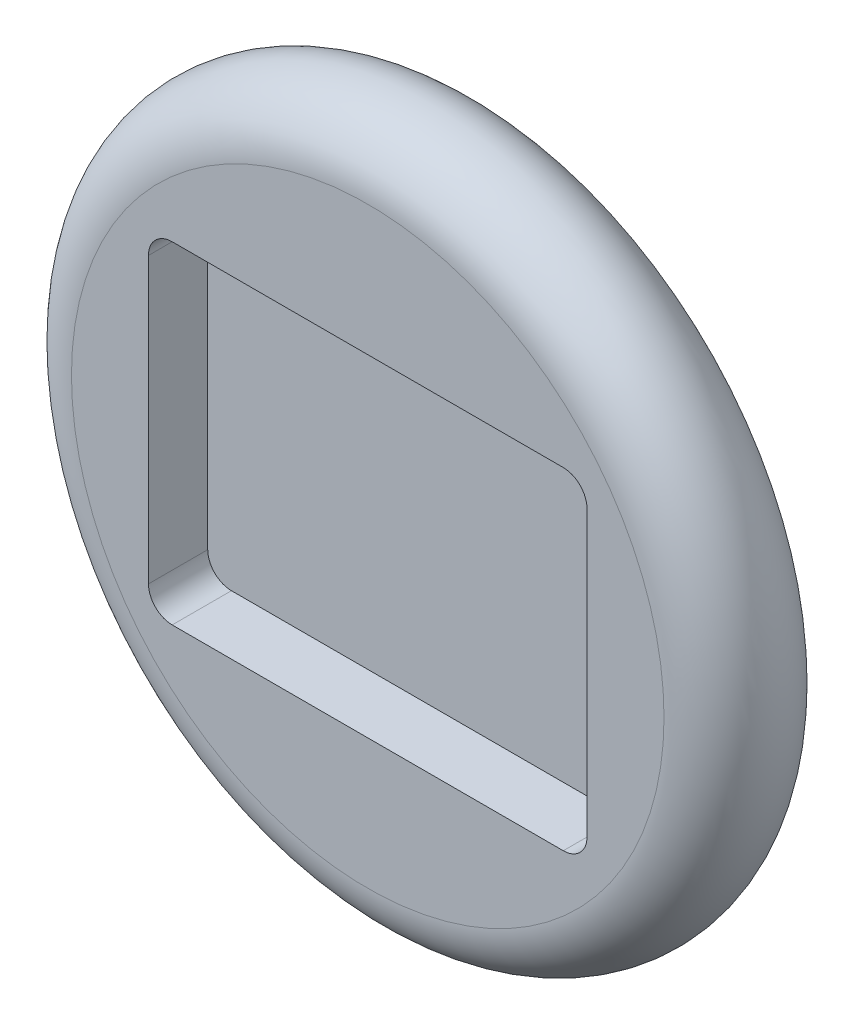
SolidWorks part; units mm, degrees
ref_plane "Front Plane" through (0, 0, 0) normal (0, 0, 1) x (1, 0, 0)
ref_plane "Top Plane" through (0, 0, 0) normal (0, 1, 0) x (1, 0, 0)
ref_plane "Right Plane" through (0, 0, 0) normal (1, 0, 0) x (0, 0, -1)
sketch "Sketch7" plane through (0, 0, 0) normal (0, 1, 0) x (1, 0, 0)
  line L0 (0, -2.5) -> (0, 7.5)
  line L4 (0, -2.5) -> (25, -2.5)
  line L5 (0, 7.5) -> (25, 7.5)
  line L6 (25, -2.5) -> (25, 7.5) construction
  arc A2 (25, -2.5) -> (25, 7.5) centre (25, 2.5) ccw
  point P0 (0, 0)
  dimension "D2" = 10
  dimension "D1" = 25
revolve "Revolve2" add sketch "Sketch7" angle 360 about L0
ref_plane "Plane2" through (0, 0, 2.5) normal (0, 0, 1) x (1, 0, 0)
sketch "Sketch9" plane through (0, 0, 2.5) normal (0, 0, 1) x (1, 0, 0)
  line L1 (16.5, -14) -> (-16.5, -14)
  line L2 (18.5, -12) -> (18.5, 12)
  line L3 (16.5, 14) -> (-16.5, 14)
  line L4 (-18.5, -12) -> (-18.5, 12)
  line L5 (18.5, -14) -> (-18.5, 14) construction
  line L6 (18.5, 14) -> (-18.5, -14) construction
  arc A0 (18.5, 12) -> (16.5, 14) centre (16.5, 12) ccw
  arc A1 (18.5, -12) -> (16.5, -14) centre (16.5, -12) cw
  arc A2 (-16.5, -14) -> (-18.5, -12) centre (-16.5, -12) cw
  arc A3 (-18.5, 12) -> (-16.5, 14) centre (-16.5, 12) cw
  point P0 (0, 0)
  dimension "D3" = 2
  dimension "D1" = 37
  dimension "D2" = 28
extrude "Cut-Extrude3" cut sketch "Sketch9" against normal blind 5
